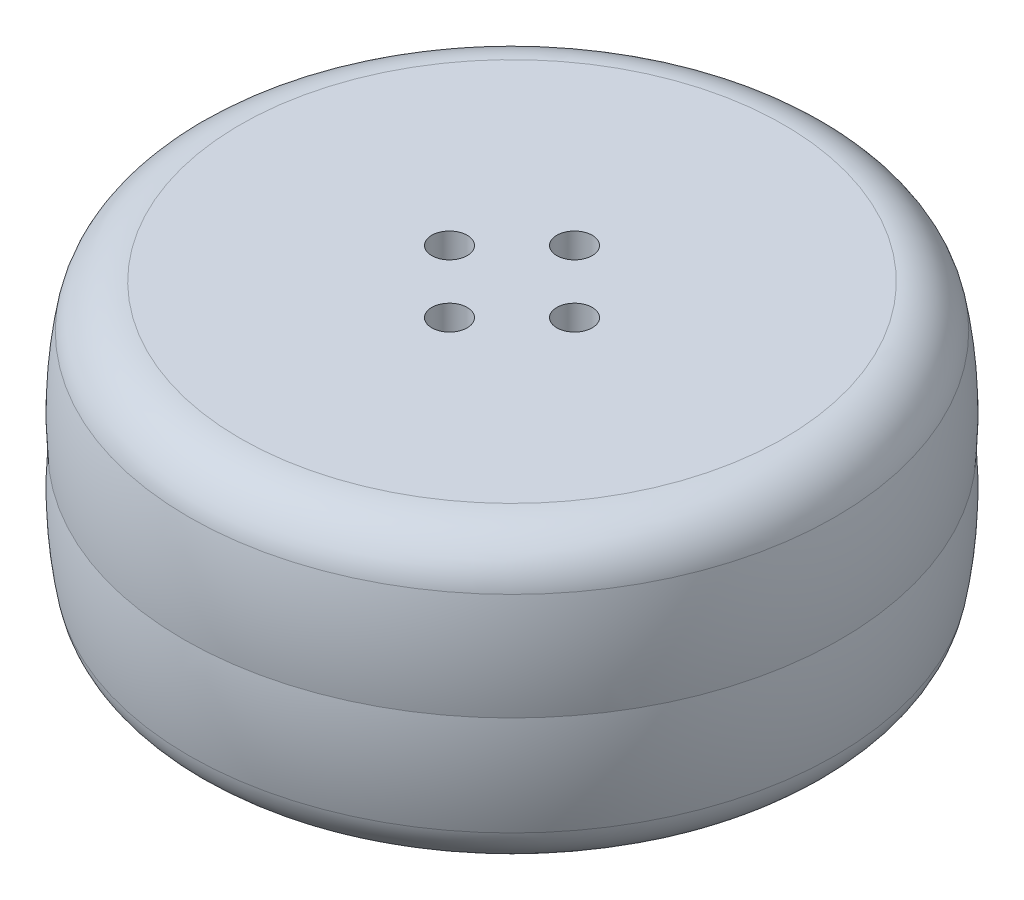
SolidWorks part; units mm, degrees
ref_plane "Front Plane" through (0, 0, 0) normal (0, 0, 1) x (1, 0, 0)
ref_plane "Top Plane" through (0, 0, 0) normal (0, 1, 0) x (1, 0, 0)
ref_plane "Right Plane" through (0, 0, 0) normal (1, 0, 0) x (0, 0, -1)
sketch "Sketch1" plane through (0, 0, 0) normal (1, 0, 0) x (0, 0, -1)
  line L0 (0, -17.9587) -> (0, -31.9587)
  line L1 (0, -31.9587) -> (31.5, -31.9587)
  line L2 (0, -17.9587) -> (26.0781, -17.9587)
  arc A0 (26.0781, -17.9587) -> (30.9941, -22.0459) centre (26.0781, -22.9587) cw
  spline S0 degree 3 poles (30.9941, -22.0459) (31.6, -25.3089) (31.7712, -28.6448) (31.5, -31.9587) knots 0.295651 0.295651 0.295651 0.295651 1 1 1 1
  dimension "D2" = 31.5
  dimension "D3" = 5
  dimension "D1" = 14
revolve "Revolve1" add sketch "Sketch1" angle 360 about L0
ref_plane "Plane1" through (0, -31.9587, 0) normal (0, -1, 0) x (-1, 0, 0)
mirror "Mirror1" about plane through (0, -31.9587, 0) normal (0, -1, 0) of "Revolve1"
sketch "Sketch2" plane through (0, -17.9587, 0) normal (0, 1, 0) x (1, 0, 0)
  circle A0 centre (-6, 0) radius 1.7
  circle A1 centre (0, 6) radius 1.7
  circle A2 centre (6, 0) radius 1.7
  circle A3 centre (0, -6) radius 1.7
  point P12 (0, 0)
  dimension "D1" = 3.4
  dimension "D2" = 6
  dimension "D3" = 4
extrude "Cut-Extrude1" cut sketch "Sketch2" against normal blind 10
sketch "Sketch3" plane through (0, -45.9587, 0) normal (0, -1, 0) x (1, 0, 0)
  line L0 (0, 20.4024) -> (0, -18.761) construction
  circle A0 centre (-21.59, -2.7823) radius 1.7514
  circle A1 centre (0, 19.5697) radius 1.7514
  circle A2 centre (21.59, -2.7823) radius 1.7514
  point P9 (0, 0)
  dimension "D1" = 21.59
  dimension "D2" = 22.352
extrude "Cut-Extrude2" cut sketch "Sketch3" against normal blind 10
